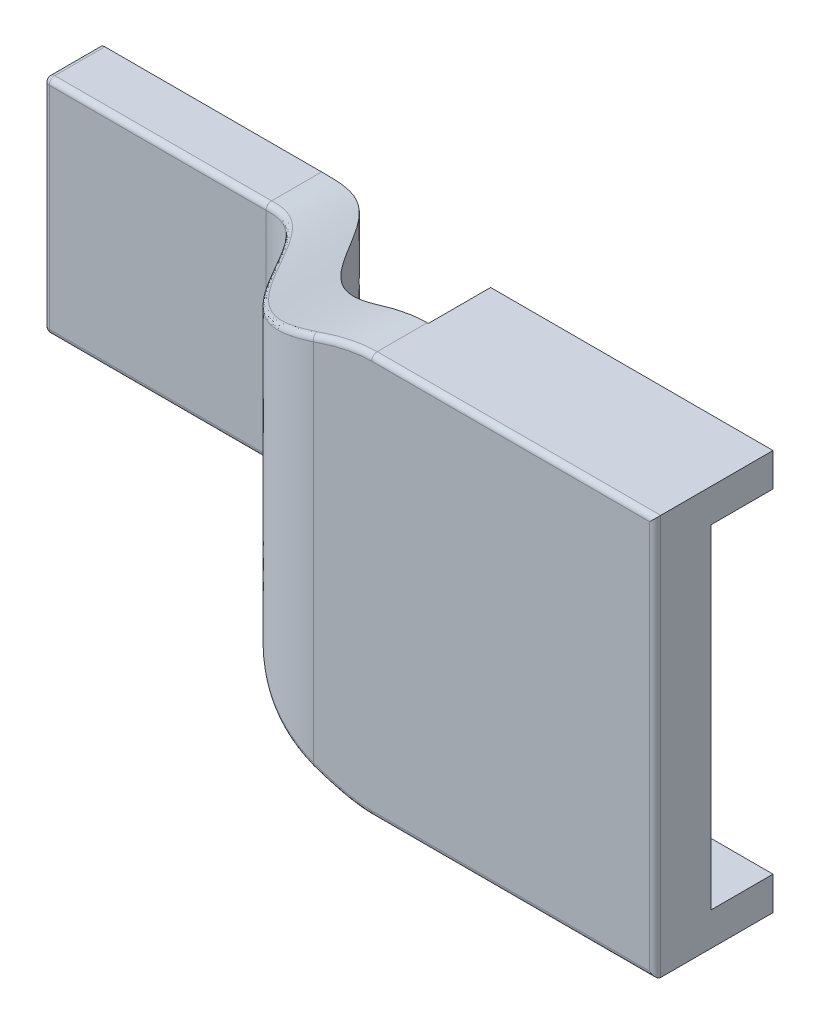
SolidWorks part; units mm, degrees
ref_plane "Plan de face" through (0, 0, 0) normal (0, 0, 1) x (1, 0, 0)
ref_plane "Plan de dessus" through (0, 0, 0) normal (0, 1, 0) x (1, 0, 0)
ref_plane "Plan de droite" through (0, 0, 0) normal (1, 0, 0) x (0, 0, -1)
sketch "Esquisse1" plane through (0, 0, 0) normal (0, 0, 1) x (1, 0, 0)
  line L1 (0, 0) -> (25.4, 0)
  line L2 (0, 0) -> (0, 36)
  line L3 (0, 36) -> (25.4, 36)
  line L4 (25.4, 0) -> (25.4, 36)
  line L5 (25.4, 36) -> (-44.6, 36)
  line L6 (25.4, 36) -> (25.4, 0)
  line L7 (25.4, 0) -> (-44.6, 0)
  line L8 (-44.6, 36) -> (-44.6, 0)
  dimension "D1" = 25.4
  dimension "D2" = 36
  dimension "D3" = 70
  dimension "D4" = 36
extrude "Boss.-Extru.1" add sketch "Esquisse1" along normal blind 5 contours L5 L8 L7 L2 | L1 L4 L3 L2
sketch "Esquisse2" plane through (0, 0, 0) normal (0, 0, -1) x (-1, 0, 0)
  line L1 (-25.4, 0) -> (0, 0)
  line L2 (-25.4, 0) -> (-25.4, 3)
  line L3 (-25.4, 3) -> (0, 3)
  line L4 (0, 0) -> (0, 3)
  line L5 (-25.4, 36) -> (0, 36)
  line L6 (-25.4, 36) -> (-25.4, 33)
  line L7 (-25.4, 33) -> (0, 33)
  line L8 (0, 36) -> (0, 33)
extrude "Boss.-Extru.2" add sketch "Esquisse2" along normal blind 5.6
sketch "Esquisse3" plane through (0, 0, 0) normal (0, 0, -1) x (-1, 0, 0)
  line L0 (0, 36) -> (44.6, 36) construction
  line L1 (44.6, 0) -> (4.6, 0)
  line L2 (44.6, 0) -> (44.6, 36)
  line L3 (44.6, 36) -> (4.6, 36)
  line L4 (4.6, 0) -> (4.6, 36)
  dimension "D1" = 40
extrude "Boss.-Extru.4" add sketch "Esquisse3" along normal blind 15
sketch "Esquisse4" plane through (0, 36, 0) normal (0, 1, 0) x (1, 0, 0)
  line L0 (25.4, -5) -> (-44.6, -5) construction
  line L2 (-44.6, 15) -> (-44.6, -5)
  line L3 (-44.6, -5) -> (-9.6, -5)
  line L6 (-44.6, 15) -> (-24.6, 15)
  line L7 (-44.6, 15) -> (-44.6, 10)
  line L8 (-44.6, 10) -> (-24.6, 10)
  line L9 (-24.6, 15) -> (-24.6, 10)
  line L10 (-44.6, 15) -> (-4.6, 15)
  line L11 (-44.6, 15) -> (-44.6, -5)
  line L12 (-44.6, -5) -> (-4.6, -5)
  line L13 (-4.6, 15) -> (-4.6, -5)
  spline S0 degree 3 poles (-4.6, 0) (-13.7723, 0.3187) (-15.5463, 14.9748) (-24.6, 15) knots 0 0 0 0 1 1 1 1
  spline S1 degree 3 poles (-24.6, 10) (-18.4548, 10.2557) (-16.4546, -5.3224) (-4.6, -5) knots 0 0 0 0 1 1 1 1
  line M11 (-4.6, 0) -> (-4.6, 15)
  line M12 (-4.6, 15) -> (-44.6, 15)
  line M14 (-44.6, -5) -> (25.4, -5)
  dimension "D1" = 20
  dimension "D2" = 5
  dimension "D3" = 40
extrude "Enlèv. mat.-Extru.3" cut sketch "Esquisse4" against normal through all contours S1 L8 L2 M14 | S0 M11 M12
sketch "Esquisse7" plane through (0, 0, -15) normal (0, 0, -1) x (-1, 0, 0)
  line L0 (44.6, 0) -> (44.6, 8) construction
  line L1 (44.6, 0) -> (44.6, 36) construction
  line L3 (44.6, 8) -> (24.6, 8)
  line L4 (44.6, 8) -> (44.6, 28)
  line L5 (44.6, 28) -> (24.6, 28)
  line L6 (24.6, 8) -> (24.6, 28)
  line L7 (44.6, 0) -> (0.1, 0)
  line L8 (44.6, 0) -> (44.6, 36)
  line L9 (44.6, 36) -> (0.1, 36)
  line L10 (0.1, 0) -> (0.1, 36)
  spline S0 degree 3 poles (0.1, 0) (6.7667, 0) (17.9333, 8) (24.6, 8) knots 0 0 0 0 1 1 1 1
  spline S1 degree 3 poles (24.6, 28) (17.9333, 28) (6.7667, 36) (0.1, 36) knots 0 0 0 0 1 1 1 1
  dimension "D6" = 20
  dimension "D7" = 20
  dimension "D8" = 20
  dimension "D3" = 20
  dimension "D1" = 8
  dimension "D2" = 20
  dimension "D4" = 44.5
  dimension "D5" = 36
extrude "Enlèv. mat.-Extru.4" cut sketch "Esquisse7" against normal through all
fillet "Congé4" radius 0.5 12 edges at (25.4, 18, 5) (12.65, 0, 5) (-20.4554, 7.268, -7.6097) (-34.6, 8, -10) (-44.6, 8, -12.5) (-44.6, 28, -12.5) (-44.6, 18, -10) (12.65, 36, 5) (-18.4266, 29.4221, -4.8925) (-34.6, 28, -10)
